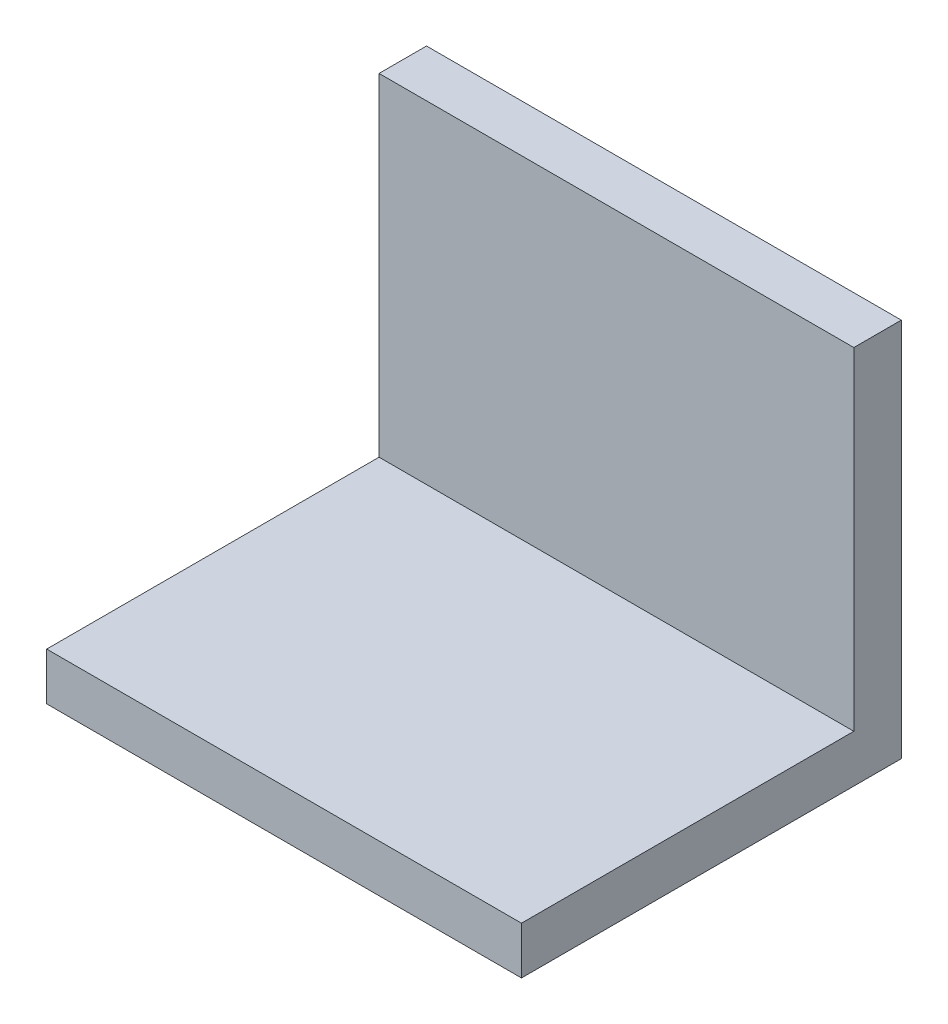
SolidWorks part; units mm, degrees
ref_plane "정면" through (0, 0, 0) normal (0, 0, 1) x (1, 0, 0)
ref_plane "윗면" through (0, 0, 0) normal (0, 1, 0) x (1, 0, 0)
ref_plane "우측면" through (0, 0, 0) normal (1, 0, 0) x (0, 0, -1)
sketch "스케치1" plane through (0, 0, 0) normal (1, 0, 0) x (0, 0, -1)
  line L0 (0, 0) -> (40, 0)
  line L1 (40, 0) -> (40, 40)
  line L2 (40, 40) -> (35, 40)
  line L3 (35, 40) -> (35, 5)
  line L4 (35, 5) -> (0, 5)
  line L5 (0, 5) -> (0, 0)
  dimension "D1" = 5
  dimension "D2" = 5
  dimension "D3" = 40
  dimension "D4" = 40
extrude "보스-돌출1" add sketch "스케치1" along normal blind 50
